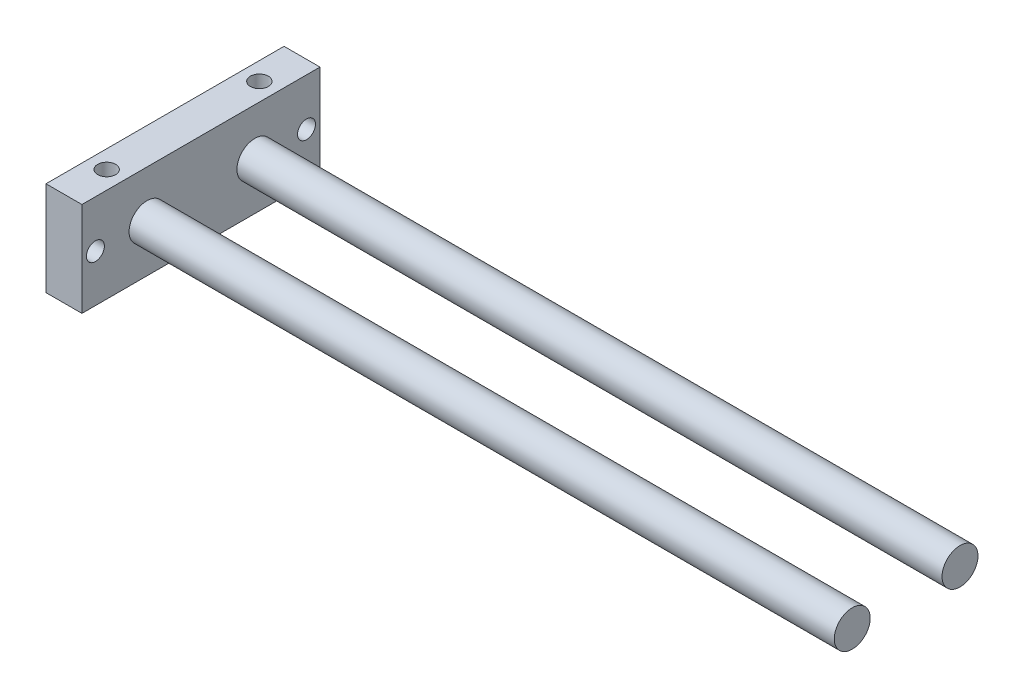
SolidWorks part; units mm, degrees
ref_plane "前视基准面" through (0, 0, 0) normal (0, 0, 1) x (1, 0, 0)
ref_plane "上视基准面" through (0, 0, 0) normal (0, 1, 0) x (1, 0, 0)
ref_plane "右视基准面" through (0, 0, 0) normal (1, 0, 0) x (0, 0, -1)
sketch "草图1" plane through (0, 0, 0) normal (1, 0, 0) x (0, 0, -1)
  line L0 (26.5, 0) -> (26.5, 21) construction
  line L1 (0, 0) -> (53, 0)
  line L2 (0, 0) -> (0, 21)
  line L3 (0, 21) -> (53, 21)
  line L4 (53, 0) -> (53, 21)
  circle A0 centre (50, 10.5) radius 2
  circle A1 centre (3, 10.5) radius 2
  dimension "D3" = 4
  dimension "D4" = 47
  dimension "D1" = 53
  dimension "D2" = 21
extrude "凸台-拉伸1" add sketch "草图1" along normal blind 8
sketch "草图2" plane through (0, 0, 0) normal (-1, 0, 0) x (0, 0, 1)
  line L0 (-26.5, 21) -> (-26.5, 0) construction
  line L1 (-53, 21) -> (0, 21) construction
  line L2 (0, 0) -> (-53, 0) construction
  circle A0 centre (-14.5, 10.5) radius 4
  circle A1 centre (-38.5, 10.5) radius 4
  dimension "D1" = 8
  dimension "D2" = 24
extrude "切除-拉伸1" cut sketch "草图2" against normal blind 5
sketch "草图3" plane through (8, 0, 0) normal (1, 0, 0) x (0, 0, -1)
  line L0 (26.5, 21) -> (26.5, 0) construction
  line L1 (53, 21) -> (0, 21) construction
  line L2 (0, 0) -> (53, 0) construction
  circle A0 centre (38.5, 10.5) radius 4
  circle A1 centre (14.5, 10.5) radius 4
  point P8 (26.5, 10.5)
  dimension "D1" = 8
  dimension "D2" = 24
extrude "凸台-拉伸2" add sketch "草图3" along normal blind 157
sketch "草图4" plane through (0, 21, 0) normal (0, 1, 0) x (1, 0, 0)
  line L0 (8, 26.5) -> (0, 26.5) construction
  line L1 (8, 53) -> (8, 0) construction
  line L2 (0, 53) -> (0, 0) construction
  circle A0 centre (4, 43.5) radius 2
  circle A1 centre (4, 9.5) radius 2
  point P6 (4, 26.5)
  dimension "D1" = 34
  dimension "D2" = 4
extrude "切除-拉伸2" cut sketch "草图4" against normal blind 5
